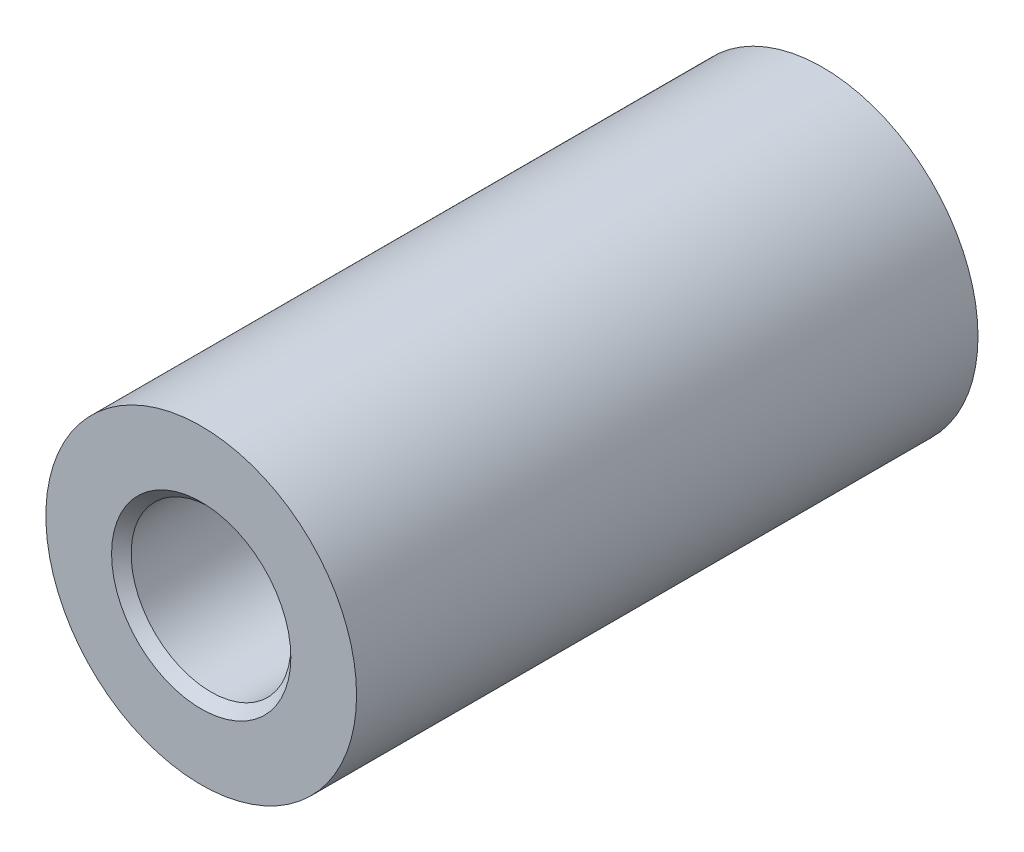
SolidWorks part; units mm, degrees
ref_plane "Front Plane" through (0, 0, 0) normal (0, 0, 1) x (1, 0, 0)
ref_plane "Top Plane" through (0, 0, 0) normal (0, 1, 0) x (1, 0, 0)
ref_plane "Right Plane" through (0, 0, 0) normal (1, 0, 0) x (0, 0, -1)
sketch "Sketch1" plane through (0, 0, 0) normal (0, 0, 1) x (1, 0, 0)
  circle A0 centre (0, 0) radius 6.35
extrude "Boss-Extrude1" add sketch "Sketch1" along normal blind 25.4
hole_wizard "F (0.257) Diameter Hole1" positions "Sketch3" profile "Sketch2" hole size "F" standard "ANSI Inch" end condition through all
sketch "Sketch3" plane through (0, 0, 25.4) normal (0, 0, 1) x (1, 0, 0)
  point P0 (0, 0)
sketch "Sketch2" plane through (0, 0, 25.4) normal (1, 0, 0) x (0, -1, 0)
  line L0 (0, 0) -> (0, 25.4)
  line L1 (0, 25.4) -> (3.2639, 25.4)
  line L2 (3.2639, 25.4) -> (3.2639, 0)
  line L5 (3.2639, 0) -> (0, 0)
  line L11 (0, -6.35) -> (0, 107.95) construction
  dimension "Thru Hole Dia." = 6.5278
  dimension "Thru Hole Depth" = 25.4
chamfer "Chamfer1" distance 0.4 angle 45 2 edges at (3.2639, 0, 0) (3.2639, 0, 25.4)
